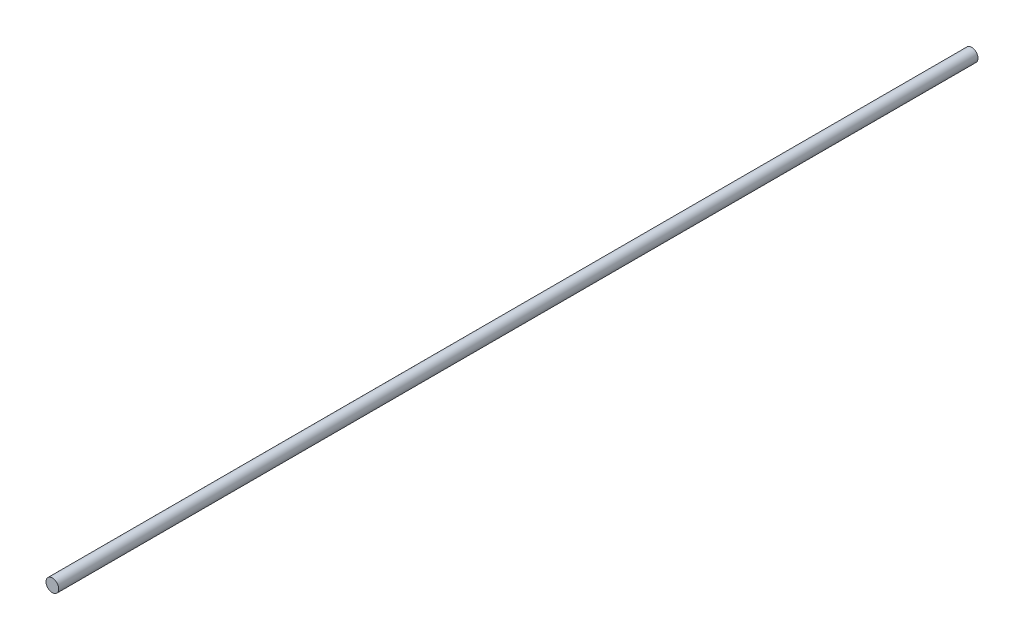
SolidWorks part; units mm, degrees
ref_plane "Front Plane" through (0, 0, 0) normal (0, 0, 1) x (1, 0, 0)
ref_plane "Top Plane" through (0, 0, 0) normal (0, 1, 0) x (1, 0, 0)
ref_plane "Right Plane" through (0, 0, 0) normal (1, 0, 0) x (0, 0, -1)
sketch "Sketch1" plane through (0, 0, 0) normal (0, 0, 1) x (1, 0, 0)
  circle A0 centre (0, 0) radius 3.175
  dimension "D1" = 6.35
extrude "Boss-Extrude1" add sketch "Sketch1" along normal mid plane 457.2
